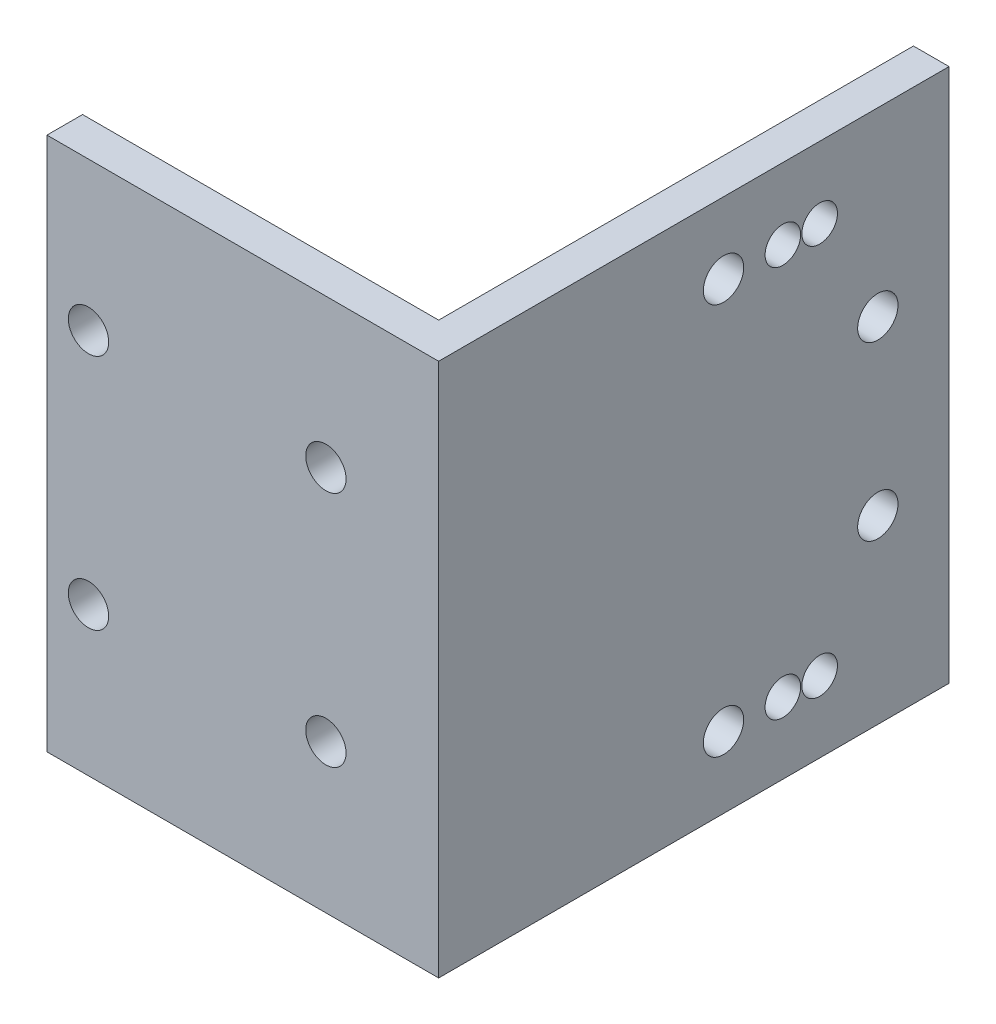
SolidWorks part; units mm, degrees
ref_plane "前视基准面" through (0, 0, 0) normal (0, 0, 1) x (1, 0, 0)
ref_plane "上视基准面" through (0, 0, 0) normal (0, 1, 0) x (1, 0, 0)
ref_plane "右视基准面" through (0, 0, 0) normal (1, 0, 0) x (0, 0, -1)
sketch "草图1" plane through (0, 0, 0) normal (0, 1, 0) x (1, 0, 0)
  line L0 (0, 0) -> (30, 0)
  line L1 (30, 0) -> (30, 60)
  line L2 (0, -3) -> (33, -3)
  line L3 (33, -3) -> (33, 60)
  line L4 (30, 60) -> (33, 60)
  line L5 (0, 0) -> (0, -3)
  dimension "D1" = 30
  dimension "D2" = 60
  dimension "D3" = 3
extrude "凸台-拉伸1" add sketch "草图1" along normal blind 45
sketch "草图2" plane through (0, 0, 3) normal (0, 0, 1) x (1, 0, 0)
  line L0 (0, 45) -> (33, 45) construction
  line L2 (0, 45) -> (0, 0) construction
  circle A0 centre (3.5, 32.5) radius 1.7
  circle A1 centre (23.5, 32.5) radius 1.7
  circle A2 centre (23.5, 12.5) radius 1.7
  circle A3 centre (3.5, 12.5) radius 1.7
  dimension "D5" = 3.4
  dimension "D1" = 20
  dimension "D2" = 20
  dimension "D3" = 12.5
  dimension "D4" = 3.5
extrude "切除-拉伸1" cut sketch "草图2" against normal up to next
sketch "草图3" plane through (33, 0, 0) normal (1, 0, 0) x (0, 0, -1)
  line L0 (-3, 0) -> (60, 0) construction
  line L1 (60, 45) -> (60, 0) construction
  line L2 (-3, 45) -> (-3, 0) construction
  line L3 (-3, 45) -> (60, 45) construction
  line L4 (-18.4473, 22.5) -> (76.5611, 22.5) construction
  circle A0 centre (21, 6) radius 1.7
  circle A1 centre (21, 39) radius 1.7
  circle A2 centre (34, 15.25) radius 1.7
  circle A3 centre (34, 29.75) radius 1.7
  circle A4 centre (26, 39) radius 1.5
  circle A5 centre (29.1, 6) radius 1.5
  circle A6 centre (29.1, 39) radius 1.5
  circle A7 centre (26, 6) radius 1.5
  dimension "D4" = 3.4
  dimension "D5" = 33
  dimension "D9" = 3
  dimension "D10" = 6
  dimension "D12" = 22.5
  dimension "D1" = 14.5
  dimension "D2" = 15.25
  dimension "D3" = 26
  dimension "D6" = 6
  dimension "D7" = 13
  dimension "D8" = 29
  dimension "D11" = 3.1
extrude "切除-拉伸2" cut sketch "草图3" against normal up to next
sketch "草图4" plane through (30, 0, 0) normal (-1, 0, 0) x (0, 0, 1)
  line L0 (-40, 45) -> (-40, 0)
  line L1 (-60, 45) -> (0, 45) construction
  line L2 (-60, 0) -> (0, 0) construction
  line L3 (-60, 45) -> (-60, 0) construction
  dimension "D1" = 20
extrude "切除-拉伸3" cut sketch "草图4" against normal through all and the other way through all flip side to cut
